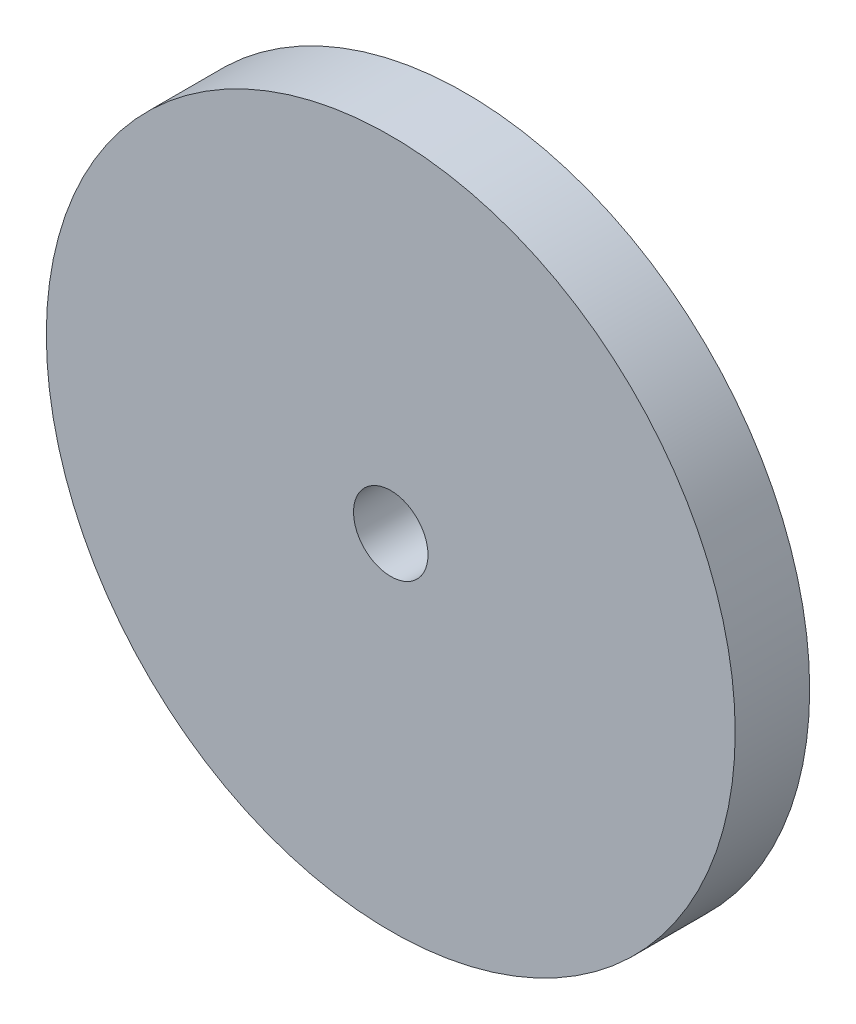
SolidWorks part; units mm, degrees
ref_plane "Front Plane" through (0, 0, 0) normal (0, 0, 1) x (1, 0, 0)
ref_plane "Top Plane" through (0, 0, 0) normal (0, 1, 0) x (1, 0, 0)
ref_plane "Right Plane" through (0, 0, 0) normal (1, 0, 0) x (0, 0, -1)
sketch "Sketch2" plane through (0, 0, 0) normal (0, 0, 1) x (1, 0, 0)
  circle A0 centre (0, 0) radius 2
  circle A1 centre (0, 0) radius 18.5
  dimension "D1" = 4
  dimension "D2" = 37
extrude "Boss-Extrude1" add sketch "Sketch2" along normal blind 4
